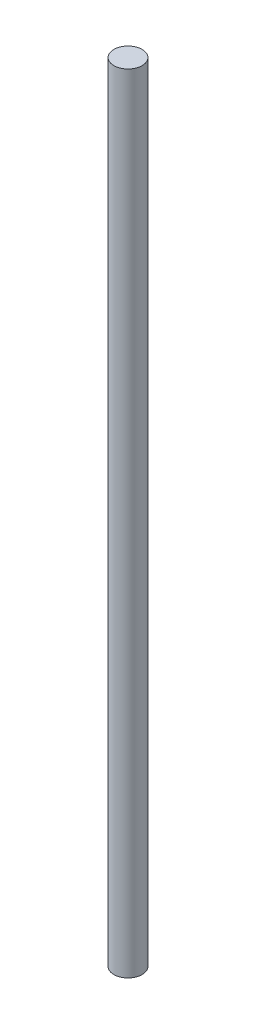
SolidWorks part; units mm, degrees
ref_plane "Front Plane" through (0, 0, 0) normal (0, 0, 1) x (1, 0, 0)
ref_plane "Top Plane" through (0, 0, 0) normal (0, 1, 0) x (1, 0, 0)
ref_plane "Right Plane" through (0, 0, 0) normal (1, 0, 0) x (0, 0, -1)
sketch "Sketch1" plane through (0, 0, 0) normal (0, 1, 0) x (1, 0, 0)
  circle A0 centre (0, 0) radius 6
  dimension "D1" = 12
extrude "Boss-Extrude1" add sketch "Sketch1" along normal blind 335
